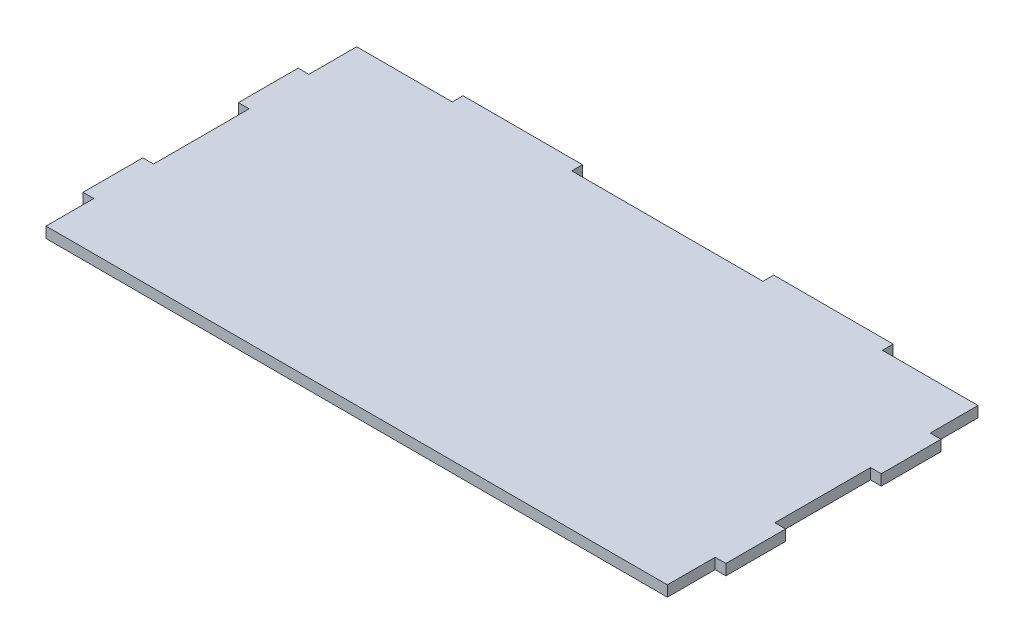
SolidWorks part; units mm, degrees
ref_plane "Front Plane" through (0, 0, 0) normal (0, 0, 1) x (1, 0, 0)
ref_plane "Top Plane" through (0, 0, 0) normal (0, 1, 0) x (1, 0, 0)
ref_plane "Right Plane" through (0, 0, 0) normal (1, 0, 0) x (0, 0, -1)
sketch "Sketch1" plane through (0, 0, 0) normal (0, 1, 0) x (1, 0, 0)
  line L0 (9.2301, 82.5125) -> (9.2301, -37.4067) construction
  line L1 (-120.7699, 92.5933) -> (-80.7699, 92.5933)
  line L2 (-120.7699, 92.5933) -> (-120.7699, 72.5933)
  line L3 (-120.7699, -37.4067) -> (139.2301, -37.4067)
  line L4 (139.2301, 92.5933) -> (139.2301, 72.5933)
  line L5 (-115.023, 27.5933) -> (139.2301, 27.5933) construction
  line L6 (99.2301, 97.0933) -> (49.2301, 97.0933)
  line L8 (-80.7699, 92.5933) -> (-80.7699, 97.0933)
  line L9 (-80.7699, 97.0933) -> (-30.7699, 97.0933)
  line L10 (-30.7699, 92.5933) -> (-30.7699, 97.0933)
  line L11 (-120.7699, 72.5933) -> (-125.2699, 72.5933)
  line L13 (-120.7699, 47.5933) -> (-125.2699, 47.5933)
  line L14 (-125.2699, 72.5933) -> (-125.2699, 47.5933)
  line L15 (49.2301, 92.5933) -> (49.2301, 97.0933)
  line L17 (99.2301, 92.5933) -> (99.2301, 97.0933)
  line L18 (-120.7699, 7.5933) -> (-125.2699, 7.5933)
  line L19 (-125.2699, -17.4067) -> (-125.2699, 7.5933)
  line L20 (-120.7699, -17.4067) -> (-125.2699, -17.4067)
  line L22 (139.2301, 47.5933) -> (143.7301, 47.5933)
  line L23 (143.7301, 72.5933) -> (143.7301, 47.5933)
  line L24 (139.2301, 72.5933) -> (143.7301, 72.5933)
  line L27 (139.2301, -17.4067) -> (143.7301, -17.4067)
  line L28 (143.7301, -17.4067) -> (143.7301, 7.5933)
  line L29 (139.2301, 7.5933) -> (143.7301, 7.5933)
  line L30 (-30.7699, 92.5933) -> (49.2301, 92.5933)
  line L31 (-120.7699, 47.5933) -> (-120.7699, 7.5933)
  line L32 (-120.7699, -17.4067) -> (-120.7699, -37.4067)
  line L33 (99.2301, 92.5933) -> (139.2301, 92.5933)
  line L34 (139.2301, 47.5933) -> (139.2301, 7.5933)
  line L35 (139.2301, -17.4067) -> (139.2301, -37.4067)
  dimension "D1" = 260
  dimension "D2" = 130
  dimension "D3" = 4.5
  dimension "D4" = 40
  dimension "D5" = 50
  dimension "D6" = 4.5
  dimension "D7" = 25
  dimension "D8" = 20
extrude "Boss-Extrude1" add sketch "Sketch1" along normal blind 4.5
